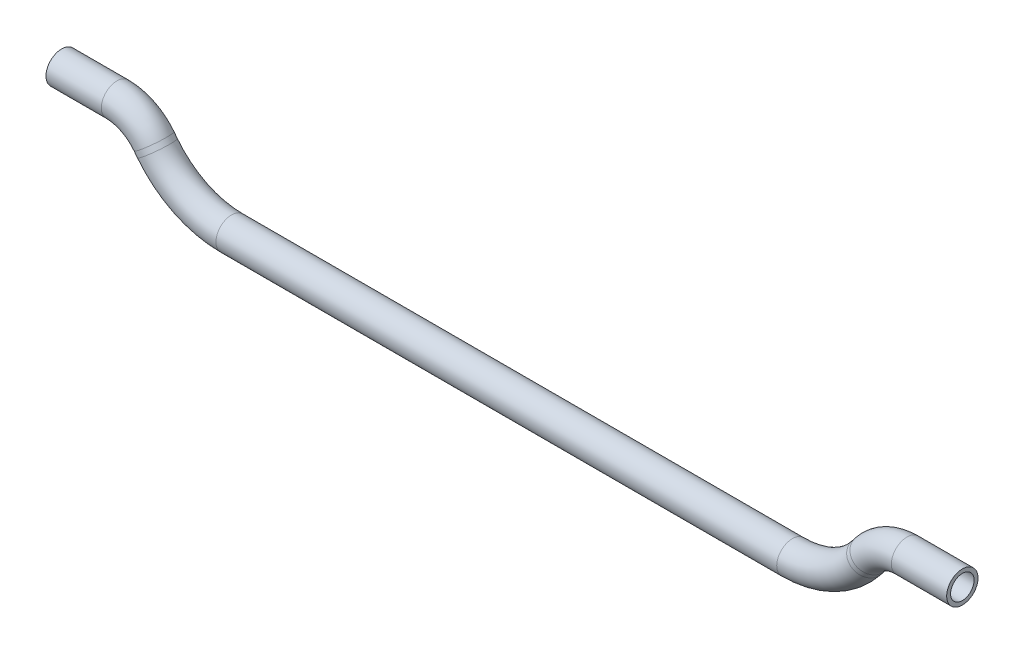
SolidWorks part; units mm, degrees
ref_plane "Front Plane" through (0, 0, 0) normal (0, 0, 1) x (1, 0, 0)
ref_plane "Top Plane" through (0, 0, 0) normal (0, 1, 0) x (1, 0, 0)
ref_plane "Right Plane" through (0, 0, 0) normal (1, 0, 0) x (0, 0, -1)
sketch "Sketch2" plane through (0, 0, 0) normal (0, 0, 1) x (1, 0, 0)
  line L0 (0, 0) -> (70.6361, 0)
  line L1 (217, -75) -> (933, -75)
  line L2 (118.0159, -23.1877) -> (122.2403, -28.6247)
  line L3 (575, -135.5274) -> (575, 59.2106) construction
  line L4 (1031.9841, -23.1877) -> (1027.7597, -28.6247)
  line L5 (1150, 0) -> (1079.3639, 0)
  arc A0 (70.6361, 0) -> (118.0159, -23.1877) centre (70.6361, -60) cw
  arc A1 (217, -75) -> (122.2403, -28.6247) centre (217, 45) cw
  arc A2 (933, -75) -> (1027.7597, -28.6247) centre (933, 45) ccw
  arc A3 (1079.3639, 0) -> (1031.9841, -23.1877) centre (1079.3639, -60) ccw
  point P7 (100, 0)
  point P18 (575, -75)
  point P19 (1050, 0)
  dimension "D4" = 60
  dimension "D5" = 120
  dimension "D1" = 75
  dimension "D2" = 575
  dimension "D3" = 100
sketch "Sketch3" plane through (0, 0, 0) normal (1, 0, 0) x (0, 0, -1)
  circle A0 centre (0, 0) radius 15
  circle A1 centre (0, 0) radius 20
  dimension "D1" = 30
  dimension "D2" = 40
sweep "Sweep1" add profiles "Sketch3" path "Sketch2"
